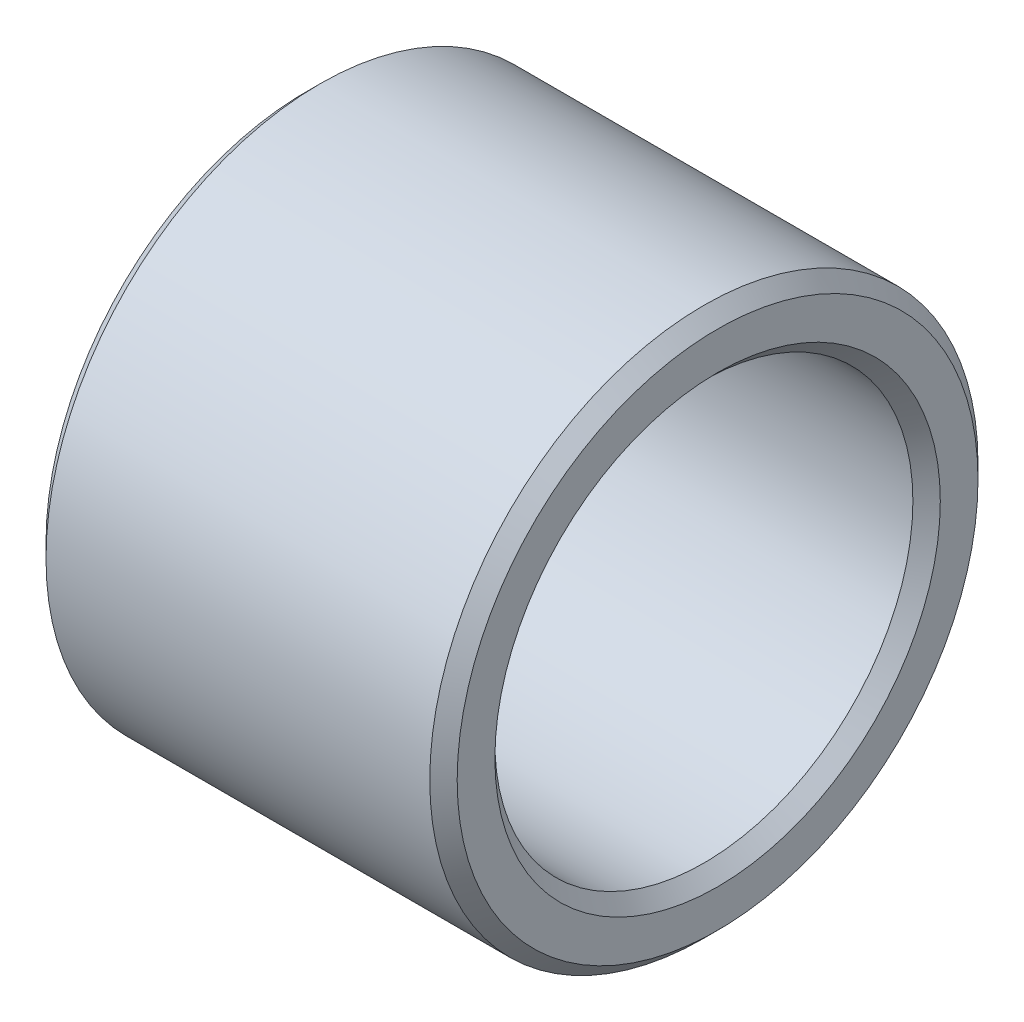
SolidWorks part; units mm, degrees
material "Латунь"
ref_plane "Спереди" through (0, 0, 0) normal (0, 0, 1) x (1, 0, 0)
ref_plane "Сверху" through (0, 0, 0) normal (0, 1, 0) x (1, 0, 0)
ref_plane "Справа" through (0, 0, 0) normal (1, 0, 0) x (0, 0, -1)
sketch "Эскиз1" plane through (0, 0, 0) normal (0, 0, 1) x (1, 0, 0)
  line L0 (0, 0) -> (-40.5451, 0) construction
  line L2 (0, 20) -> (30, 20)
  line L3 (0, 20) -> (0, 15.25)
  line L4 (0, 15.25) -> (30, 15.25)
  line L5 (30, 20) -> (30, 15.25)
  dimension "D1" = 30
  dimension "D2" = 40
  dimension "D3" = 30.5
revolve "Повернуть1" add sketch "Эскиз1" angle 360 about L0
chamfer "Фаска1" distance 1 angle 45 2 edges at (30, 0, -20) (0, 0, -20)
chamfer "Фаска2" distance 1 angle 45 2 edges at (30, 0, -15.25) (0, 0, -15.25)
